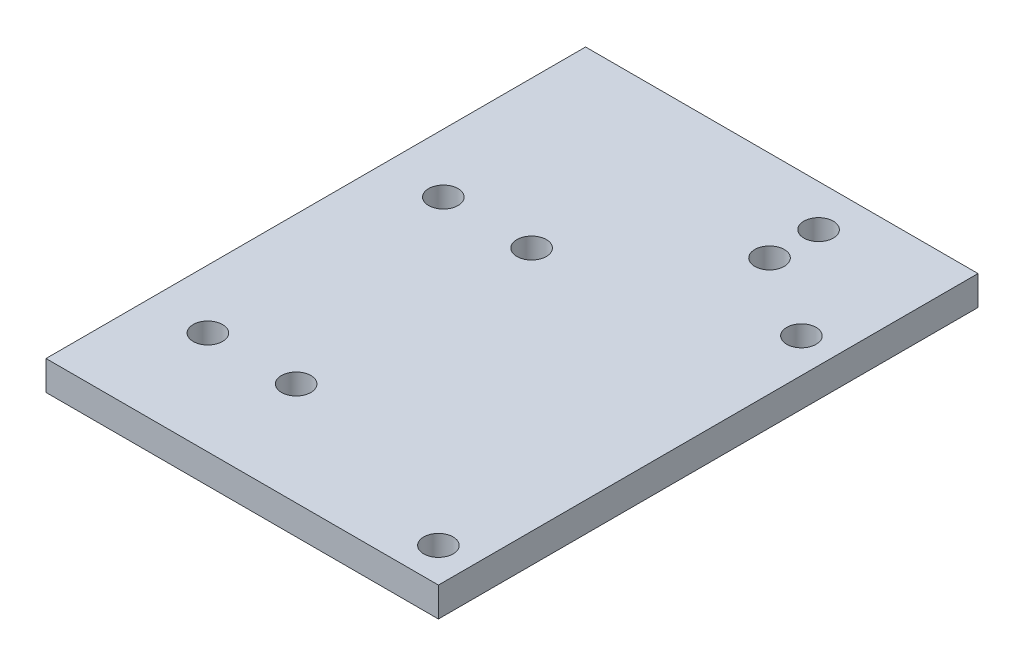
SolidWorks part; units mm, degrees
ref_plane "Front Plane" through (0, 0, 0) normal (0, 0, 1) x (1, 0, 0)
ref_plane "Top Plane" through (0, 0, 0) normal (0, 1, 0) x (1, 0, 0)
ref_plane "Right Plane" through (0, 0, 0) normal (1, 0, 0) x (0, 0, -1)
sketch "Sketch1" plane through (0, 0, 0) normal (0, 1, 0) x (1, 0, 0)
  line L1 (1.8575, 30.2374) -> (41.8575, 30.2374)
  line L2 (1.8575, 30.2374) -> (1.8575, -24.7626)
  line L3 (1.8575, -24.7626) -> (41.8575, -24.7626)
  line L4 (41.8575, 30.2374) -> (41.8575, -24.7626)
  dimension "D1" = 55
  dimension "D2" = 40
extrude "Boss-Extrude1" add sketch "Sketch1" along normal blind 3
sketch "Sketch2" plane through (0, 3, 0) normal (0, 1, 0) x (1, 0, 0)
  line L0 (1.8575, -24.7626) -> (41.8575, -24.7626) construction
  line L1 (41.8575, -24.7626) -> (41.8575, 30.2374) construction
  circle A0 centre (38.3575, -21.2626) radius 1.5
  circle A1 centre (38.3575, 15.7374) radius 1.5
  circle A2 centre (16.8575, -14.2626) radius 1.5
  circle A3 centre (7.8575, -14.2626) radius 1.5
  circle A4 centre (7.8575, 9.7374) radius 1.5
  circle A5 centre (16.8575, 9.7374) radius 1.5
  circle A6 centre (29.8575, 20.9874) radius 1.5
  circle A7 centre (29.8575, 25.9874) radius 1.5
  dimension "D1" = 3
  dimension "D2" = 3
  dimension "D7" = 3
  dimension "D10" = 3
  dimension "D13" = 3
  dimension "D14" = 3
  dimension "D19" = 3
  dimension "D22" = 3
  dimension "D3" = 3.5
  dimension "D4" = 3.5
  dimension "D5" = 3.5
  dimension "D6" = 37
  dimension "D8" = 25
  dimension "D9" = 10.5
  dimension "D11" = 10.5
  dimension "D12" = 9
  dimension "D15" = 25
  dimension "D16" = 24
  dimension "D17" = 34.5
  dimension "D18" = 9
  dimension "D20" = 45.75
  dimension "D21" = 12
  dimension "D23" = 12
  dimension "D24" = 5
extrude "Cut-Extrude1" cut sketch "Sketch2" against normal blind 3
